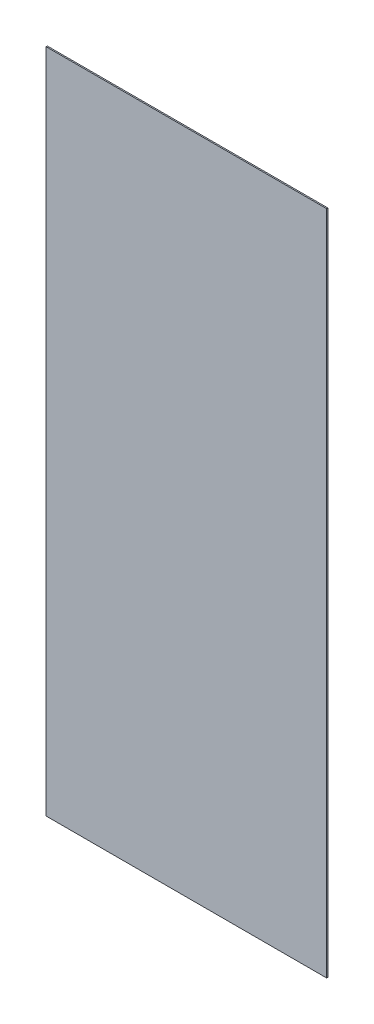
SolidWorks part; units mm, degrees
ref_plane "前视基准面" through (0, 0, 0) normal (0, 0, 1) x (1, 0, 0)
ref_plane "上视基准面" through (0, 0, 0) normal (0, 1, 0) x (1, 0, 0)
ref_plane "右视基准面" through (0, 0, 0) normal (1, 0, 0) x (0, 0, -1)
sketch "草图1" plane through (0, 0, 0) normal (0, 0, 1) x (1, 0, 0)
  line L1 (-101.6, 241.3) -> (101.6, 241.3)
  line L2 (-101.6, 241.3) -> (-101.6, -241.3)
  line L3 (-101.6, -241.3) -> (101.6, -241.3)
  line L4 (101.6, 241.3) -> (101.6, -241.3)
  line L5 (-101.6, 241.3) -> (101.6, -241.3) construction
  line L6 (-101.6, -241.3) -> (101.6, 241.3) construction
  point P0 (0, 0)
  dimension "D1" = 203.2
  dimension "D2" = 482.6
extrude "凸台-拉伸1" add sketch "草图1" along normal blind 0.9
